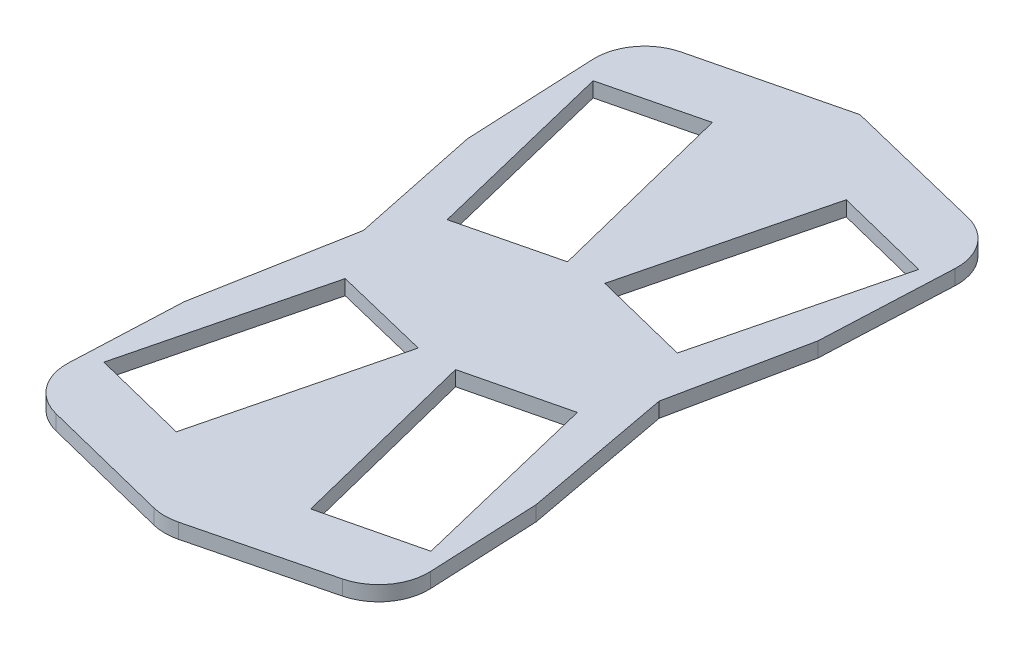
SolidWorks part; units mm, degrees
ref_plane "Alzado" through (0, 0, 0) normal (0, 0, 1) x (1, 0, 0)
ref_plane "Planta" through (0, 0, 0) normal (0, 1, 0) x (1, 0, 0)
ref_plane "Vista lateral" through (0, 0, 0) normal (1, 0, 0) x (0, 0, -1)
sketch "Croquis1" plane through (0, 0, 0) normal (0, 1, 0) x (1, 0, 0)
  line L0 (-3.75, 40.9232) -> (-23.1758, 36.1652)
  line L1 (-3.75, 40.9232) -> (-13.4515, 79.7293)
  line L2 (-35.3226, -4.5238) -> (-29.7138, 25.866)
  line L3 (-23.1758, 36.1652) -> (-32.6918, 75.0168)
  line L4 (0, 95.9232) -> (28.7456, 88.8733)
  line L5 (36.3535, 78.7092) -> (35.159, 52.308)
  line L6 (0, 95.9232) -> (-28.841, 88.8591)
  line L7 (35.159, 52.308) -> (29.6982, 25.9067)
  line L8 (-2.4254, -43.4705) -> (-28.7307, -36.8942)
  line L9 (-36.2958, -26.7554) -> (-35.3226, -4.5238)
  line L10 (-32.6918, 75.0168) -> (-13.4515, 79.7293)
  line L11 (13.454, 79.739) -> (3.75, 40.9232)
  line L13 (3.75, 40.9232) -> (23.1554, 36.0826)
  line L14 (-3.75, 10.9232) -> (-13.4746, -27.9754)
  line L15 (2.4254, -43.4705) -> (28.8038, -36.8759)
  line L16 (23.1554, 36.0826) -> (32.8568, 74.8883)
  line L17 (36.368, -26.7182) -> (35.353, -4.4924)
  line L18 (-35.2218, 52.2736) -> (-29.7138, 25.866)
  line L19 (32.8568, 74.8883) -> (13.454, 79.739)
  line L20 (-36.4512, 78.6812) -> (-35.2218, 52.2736)
  line L21 (35.353, -4.4924) -> (29.6982, 25.9067)
  line L22 (3.75, 40.9232) -> (23.1554, 36.0826)
  line L23 (3.75, 10.9232) -> (23.4494, 15.7061)
  line L24 (23.4494, 15.7061) -> (32.887, -23.1646)
  line L25 (32.887, -23.1646) -> (13.4516, -27.8834)
  line L26 (13.4516, -27.8834) -> (3.75, 10.9232)
  line L27 (-13.4746, -27.9754) -> (-32.8775, -23.1247)
  line L28 (-32.8775, -23.1247) -> (-23.1761, 15.681)
  line L29 (-23.1761, 15.681) -> (-3.75, 10.9232)
  line L30 (-3.75, 10.9232) -> (-3.8527, 11.041)
  circle A0 centre (-20.6927, 67.6601) radius 1.5
  circle A1 centre (20.73, 67.6122) radius 1.5
  circle A2 centre (-20.7507, -15.8486) radius 1.5
  circle A3 centre (20.8099, -15.8064) radius 1.5
  arc A20 (28.7456, 88.8733) -> (36.3535, 78.7092) centre (26.3637, 79.1612) cw
  arc A21 (-28.841, 88.8591) -> (-36.4512, 78.6812) centre (-26.462, 79.1462) ccw
  arc A22 (28.8038, -36.8759) -> (36.368, -26.7182) centre (26.3784, -27.1745) ccw
  arc A23 (-28.7307, -36.8942) -> (-36.2958, -26.7554) centre (-26.3053, -27.1927) cw
  arc A24 (-2.4254, -43.4705) -> (2.4254, -43.4705) centre (0, -33.7691) ccw
  dimension "D1" = 10
  dimension "D2" = 10
  dimension "D3" = 10
extrude "Saliente-Extruir1" add sketch "Croquis1" along normal blind 3
